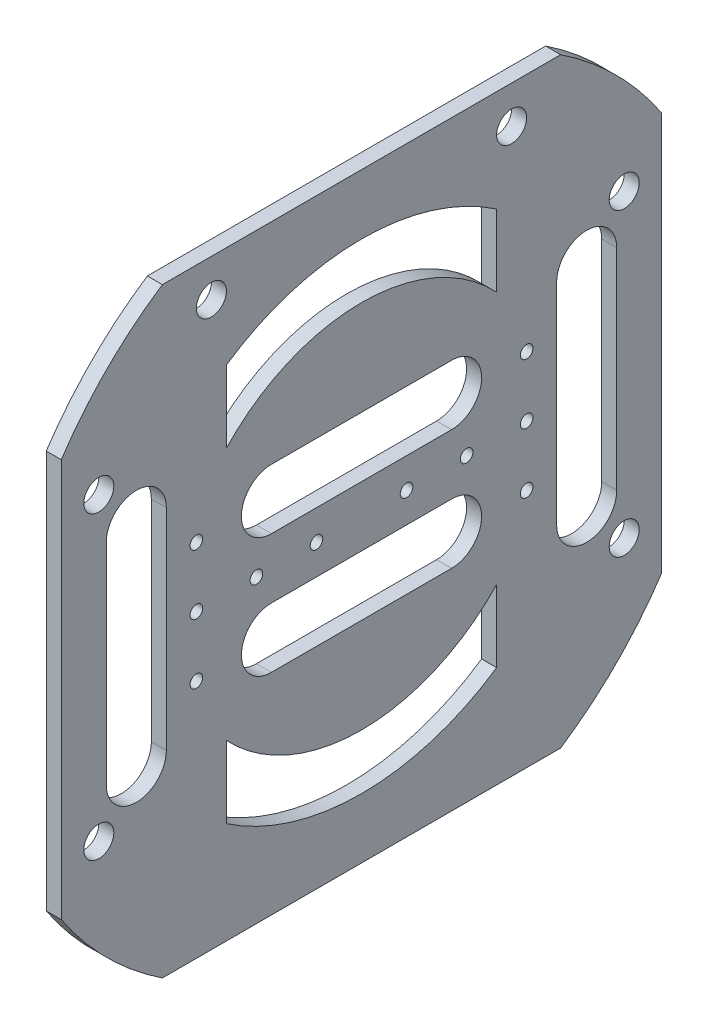
SolidWorks part; units mm, degrees
ref_plane "前视基准面" through (0, 0, 0) normal (0, 0, 1) x (1, 0, 0)
ref_plane "上视基准面" through (0, 0, 0) normal (0, 1, 0) x (1, 0, 0)
ref_plane "右视基准面" through (0, 0, 0) normal (1, 0, 0) x (0, 0, -1)
sketch "草图1" plane through (0, 0, 0) normal (1, 0, 0) x (0, 0, -1)
  line L0 (0, 87.5) -> (0, -87.5) construction
  line L1 (-100, 100) -> (100, 100)
  line L2 (-100, 100) -> (-100, -100)
  line L3 (-100, -100) -> (100, -100)
  line L4 (100, 100) -> (100, -100)
  line L5 (-100, 100) -> (100, -100) construction
  line L6 (-100, -100) -> (100, 100) construction
  line L7 (-87.5, 87.5) -> (87.5, 87.5) construction
  line L8 (-87.5, 87.5) -> (-87.5, -87.5) construction
  line L9 (-87.5, -87.5) -> (87.5, -87.5) construction
  line L10 (87.5, 87.5) -> (87.5, -87.5) construction
  line L11 (-87.5, 87.5) -> (87.5, -87.5) construction
  line L12 (-87.5, -87.5) -> (87.5, 87.5) construction
  circle A0 centre (-50, 87.5) radius 5
  circle A1 centre (50, 87.5) radius 5
  circle A2 centre (-87.5, 50) radius 5
  circle A3 centre (-87.5, -50) radius 5
  circle A4 centre (87.5, -50) radius 5
  circle A5 centre (87.5, 50) radius 5
  point P0 (0, 0)
  point P5 (0, 0)
  point P15 (0, 87.5)
  point P20 (-87.5, 0)
  dimension "D5" = 10
  dimension "D6" = 10
  dimension "D9" = 10
  dimension "D10" = 10
  dimension "D1" = 200
  dimension "D2" = 200
  dimension "D3" = 175
  dimension "D4" = 175
  dimension "D7" = 50
  dimension "D8" = 50
  dimension "D11" = 50
  dimension "D12" = 100
extrude "凸台-拉伸1" add sketch "草图1" along normal blind 5
sketch "草图3" plane through (5, 0, 0) normal (1, 0, 0) x (0, 0, -1)
  line L0 (-45, 80) -> (-45, -80) construction
  line L1 (-65, 80) -> (65, 80) construction
  line L2 (-65, 80) -> (-65, -80) construction
  line L3 (-65, -80) -> (65, -80) construction
  line L4 (65, 80) -> (65, -80) construction
  line L5 (-65, 80) -> (65, -80) construction
  line L6 (-65, -80) -> (65, 80) construction
  line L7 (45, 80) -> (45, -80) construction
  line L8 (-45, 10) -> (45, 10) construction
  line L9 (-45, -10) -> (45, -10) construction
  line L10 (-100, 0) -> (100, 0) construction
  line L11 (-100, 100) -> (-100, -100) construction
  line L12 (100, -100) -> (100, 100) construction
  line L13 (-45, 66.1438) -> (-45, 42.1438)
  line L14 (45, 66.1438) -> (45, 42.1438)
  line L15 (-45, -66.1438) -> (-45, -42.1438)
  line L16 (45, -66.1438) -> (45, -42.1438)
  line L17 (-100, -100) -> (100, -100) construction
  line L18 (-100, -66.3325) -> (-100, -100)
  line L19 (-100, -100) -> (-66.3325, -100)
  line L20 (66.3325, -100) -> (100, -100)
  line L21 (100, -100) -> (100, -66.3325)
  line L22 (66.3325, 100) -> (100, 100)
  line L23 (100, 100) -> (100, 66.3325)
  line L24 (-100, 66.3325) -> (-100, 100)
  line L25 (-100, 100) -> (-66.3325, 100)
  line L26 (-75, 35) -> (-75, -35) construction
  line L27 (-65, 35) -> (-65, -35)
  line L28 (-85, 35) -> (-85, -35)
  line L29 (0, 80) -> (0, -80) construction
  line L30 (75, 35) -> (75, -35) construction
  line L31 (65, 35) -> (65, -35)
  line L32 (85, 35) -> (85, -35)
  line L33 (-30, 20) -> (30, 20) construction
  line L34 (-30, 30) -> (30, 30)
  line L35 (-30, 10) -> (30, 10)
  line L36 (-30, -20) -> (30, -20) construction
  line L37 (-30, -30) -> (30, -30)
  line L38 (-30, -10) -> (30, -10)
  circle A0 centre (-55, 20) radius 2.1
  circle A1 centre (-55, 0) radius 2.1
  circle A2 centre (-55, -20) radius 2.1
  circle A9 centre (55, 0) radius 2.1
  circle A10 centre (55, 20) radius 2.1
  circle A11 centre (55, -20) radius 2.1
  circle A12 centre (-35, 0) radius 2.1
  circle A13 centre (-15, 0) radius 2.1
  circle A14 centre (35, 0) radius 2.1
  circle A15 centre (15, 0) radius 2.1
  arc A16 (-45, 66.1438) -> (45, 66.1438) centre (0, 0) cw
  arc A17 (-45, 42.1438) -> (45, 42.1438) centre (0, 0) cw
  arc A18 (-45, -66.1438) -> (45, -66.1438) centre (0, 0) ccw
  arc A19 (-45, -42.1438) -> (45, -42.1438) centre (0, 0) ccw
  arc A20 (-66.3325, -100) -> (-100, -66.3325) centre (0, 0) cw
  arc A21 (66.3325, -100) -> (100, -66.3325) centre (0, 0) ccw
  arc A22 (66.3325, 100) -> (100, 66.3325) centre (0, 0) cw
  arc A23 (-66.3325, 100) -> (-100, 66.3325) centre (0, 0) ccw
  arc A24 (-65, 35) -> (-85, 35) centre (-75, 35) ccw
  arc A25 (-85, -35) -> (-65, -35) centre (-75, -35) ccw
  arc A26 (65, 35) -> (85, 35) centre (75, 35) cw
  arc A27 (85, -35) -> (65, -35) centre (75, -35) cw
  arc A28 (-30, 30) -> (-30, 10) centre (-30, 20) ccw
  arc A29 (30, 10) -> (30, 30) centre (30, 20) ccw
  arc A30 (-30, -30) -> (-30, -10) centre (-30, -20) cw
  arc A31 (30, -10) -> (30, -30) centre (30, -20) cw
  point P0 (0, 0)
  point P14 (45, 0)
  point P17 (-45, 0)
  point P69 (-75, 0)
  point P78 (75, 0)
  point P85 (0, 20)
  point P90 (0, 0)
  point P91 (0, 20)
  point P94 (0, -20)
  point P99 (45, 55.3846)
  point P100 (0, 0)
  point P101 (0, 0)
  point P102 (0, 0)
  point P103 (45, -38.418)
  dimension "D7" = 4.2
  dimension "D11" = 20
  dimension "D14" = 4.2
  dimension "D15" = 4.2
  dimension "D20" = 4.2
  dimension "D23" = 24
  dimension "D24" = 10
  dimension "D27" = 10
  dimension "D29" = 120
  dimension "D30" = 120
  dimension "D1" = 160
  dimension "D2" = 130
  dimension "D3" = 20
  dimension "D4" = 20
  dimension "D5" = 10
  dimension "D6" = 20
  dimension "D8" = 10
  dimension "D9" = 20
  dimension "D13" = 20
  dimension "D16" = 20
  dimension "D17" = 20
  dimension "D18" = 10
  dimension "D19" = 10
  dimension "D22" = 20
  dimension "D25" = 15
  dimension "D26" = 70
  dimension "D28" = 60
  dimension "D10" = 3
  dimension "D12" = 3
  dimension "D21" = 3
extrude "切除-拉伸2" cut sketch "草图3" against normal through all
